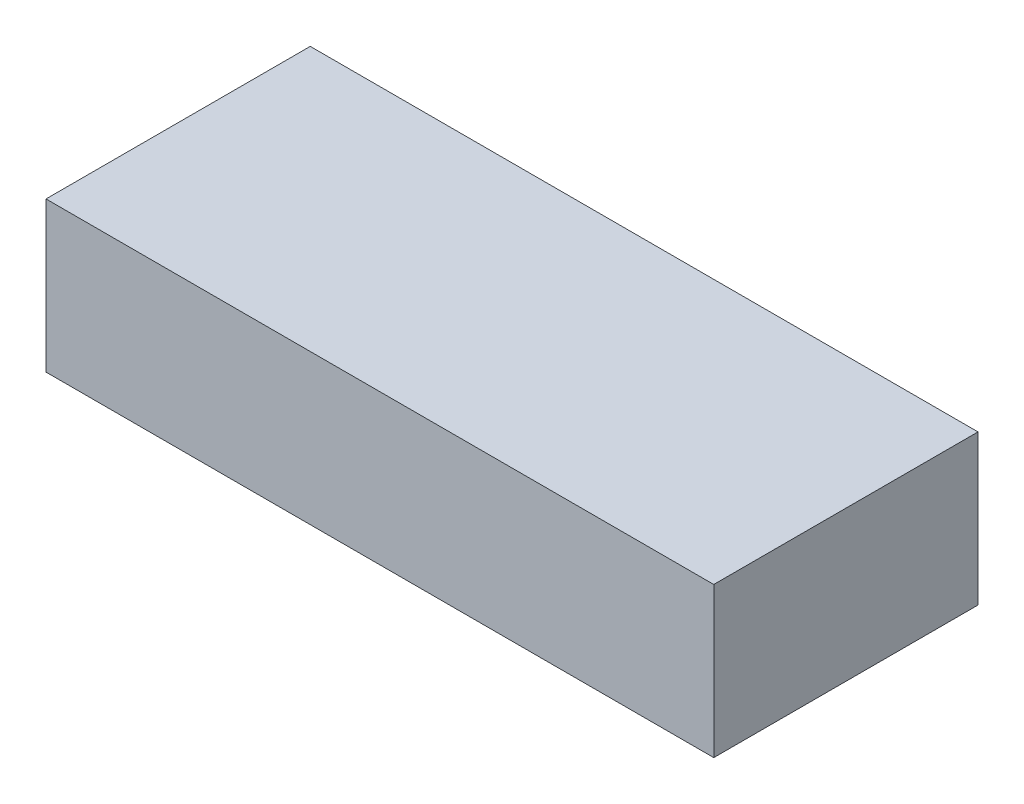
SolidWorks part; units mm, degrees
ref_plane "Front Plane" through (0, 0, 0) normal (0, 0, 1) x (1, 0, 0)
ref_plane "Top Plane" through (0, 0, 0) normal (0, 1, 0) x (1, 0, 0)
ref_plane "Right Plane" through (0, 0, 0) normal (1, 0, 0) x (0, 0, -1)
sketch "Sketch1" plane through (0, 0, 0) normal (0, 1, 0) x (1, 0, 0)
  line L1 (467.5, 0) -> (-467.5, 0)
  line L2 (467.5, 0) -> (467.5, 370)
  line L3 (467.5, 370) -> (-467.5, 370)
  line L4 (-467.5, 0) -> (-467.5, 370)
  point P4 (0, 0)
  point P6 (0, 370)
  dimension "D1" = 935
  dimension "D2" = 370
extrude "Boss-Extrude1" add sketch "Sketch1" against normal blind 210
